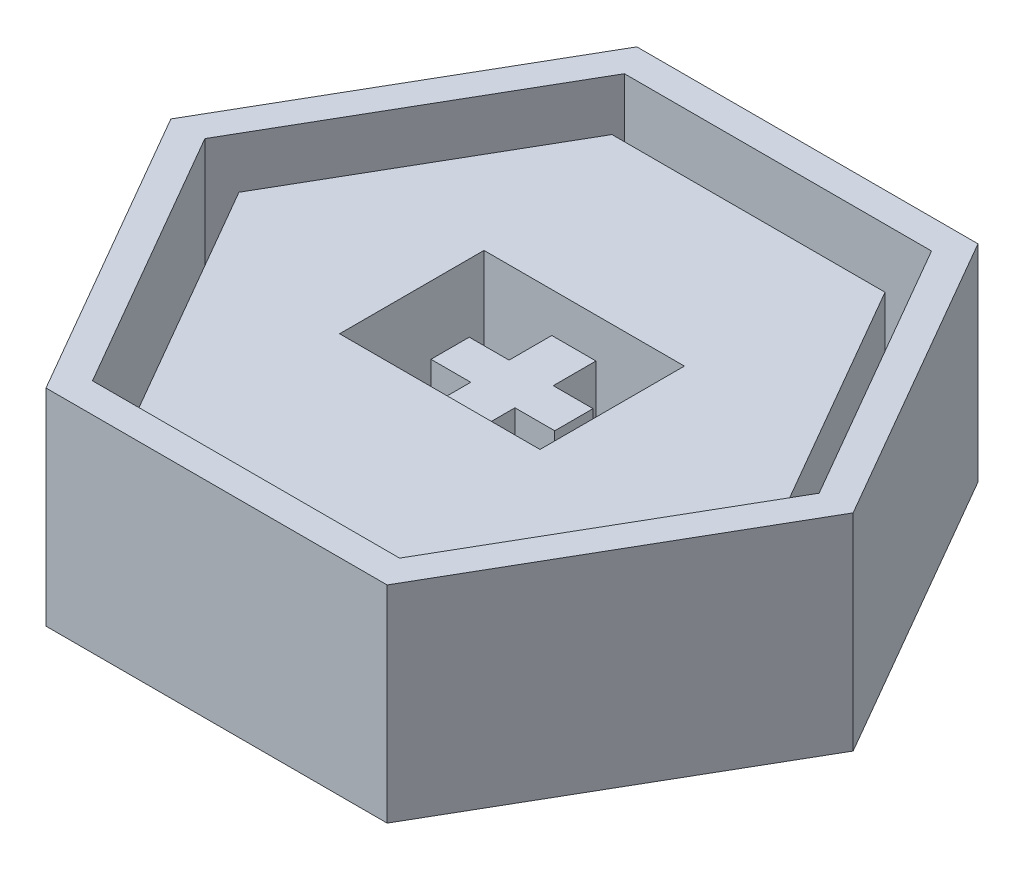
SolidWorks part; units mm, degrees
ref_plane "Plan de face" through (0, 0, 0) normal (0, 0, 1) x (1, 0, 0)
ref_plane "Plan de dessus" through (0, 0, 0) normal (0, 1, 0) x (1, 0, 0)
ref_plane "Plan de droite" through (0, 0, 0) normal (1, 0, 0) x (0, 0, -1)
sketch "Sketch1" plane through (0, 0, 0) normal (0, 1, 0) x (1, 0, 0)
  line L1 (10.4212, 0) -> (5.2106, 9.025)
  line L2 (5.2106, 9.025) -> (-5.2106, 9.025)
  line L3 (-5.2106, 9.025) -> (-10.4212, 0)
  line L4 (-10.4212, 0) -> (-5.2106, -9.025)
  line L5 (-5.2106, -9.025) -> (5.2106, -9.025)
  line L6 (5.2106, -9.025) -> (10.4212, 0)
  circle A0 centre (0, 0) radius 9.025 construction
  dimension "D1" = 18.05
extrude "Boss-Extrude1" add sketch "Sketch1" along normal blind 1
sketch "Sketch2" plane through (0, 0, 0) normal (0, -1, 0) x (1, 0, 0)
  line L1 (11.5759, 0) -> (5.7879, 10.025)
  line L2 (5.7879, 10.025) -> (-5.7879, 10.025)
  line L3 (-5.7879, 10.025) -> (-11.5759, 0)
  line L4 (-11.5759, 0) -> (-5.7879, -10.025)
  line L5 (-5.7879, -10.025) -> (5.7879, -10.025)
  line L6 (10.4212, 0) -> (5.2106, 9.025)
  line L7 (5.2106, 9.025) -> (-5.2106, 9.025)
  line L8 (-5.2106, 9.025) -> (-10.4212, 0)
  line L9 (-10.4212, 0) -> (-5.2106, -9.025)
  line L10 (-5.2106, -9.025) -> (5.2106, -9.025)
  line L11 (5.2106, -9.025) -> (10.4212, 0)
  line L12 (10.4212, 0) -> (5.2106, 9.025)
  line L13 (5.2106, 9.025) -> (-5.2106, 9.025)
  line L14 (-5.2106, 9.025) -> (-10.4212, 0)
  line L15 (-10.4212, 0) -> (-5.2106, -9.025)
  line L16 (-5.2106, -9.025) -> (5.2106, -9.025)
  line L17 (5.2106, -9.025) -> (10.4212, 0)
  line L18 (5.7879, -10.025) -> (11.5759, 0)
  dimension "D1" = 0
  dimension "D2" = 1
extrude "Boss-Extrude2" add sketch "Sketch2" against normal blind 7 separate body
sketch "Sketch3" plane through (0, 1, 0) normal (0, 1, 0) x (1, 0, 0)
  line L7 (-3.4, -2.45) -> (3.4, -2.45)
  line L8 (-3.4, -2.45) -> (-3.4, 2.45)
  line L9 (-3.4, 2.45) -> (3.4, 2.45)
  line L10 (3.4, -2.45) -> (3.4, 2.45)
  line L11 (-3.4, -2.45) -> (3.4, 2.45) construction
  line L12 (4.6332, -8.025) -> (9.2665, 0)
  line L13 (9.2665, 0) -> (4.6332, 8.025)
  line L14 (4.6332, 8.025) -> (-4.6332, 8.025)
  line L15 (-4.6332, 8.025) -> (-9.2665, 0)
  line L16 (-9.2665, 0) -> (-4.6332, -8.025)
  line L17 (-4.6332, -8.025) -> (4.6332, -8.025)
  line L18 (4.6332, -8.025) -> (9.2665, 0)
  line L19 (9.2665, 0) -> (4.6332, 8.025)
  line L20 (4.6332, 8.025) -> (-4.6332, 8.025)
  line L21 (-4.6332, 8.025) -> (-9.2665, 0)
  line L22 (-9.2665, 0) -> (-4.6332, -8.025)
  line L23 (-4.6332, -8.025) -> (4.6332, -8.025)
  line L24 (-3.4, 2.45) -> (3.4, -2.45) construction
  point P0 (0, 0)
  dimension "D2" = 6.8
  dimension "D3" = 4.9
  dimension "D1" = 1
extrude "Boss-Extrude3" add sketch "Sketch3" along normal offset from surface (5 mm away) 1 up to face at (0, 7, 0)
sketch "Sketch4" plane through (0, 1, 0) normal (0, 1, 0) x (1, 0, 0)
  line L0 (0, 2.1) -> (0, -2.1) construction
  line L1 (2.1, 0) -> (-2.1, 0) construction
  line L2 (-0.75, 2.1) -> (0.75, 2.1)
  line L3 (0.75, 2.1) -> (0.75, 0.65)
  line L4 (0.75, 0.65) -> (2.1, 0.65)
  line L5 (2.1, 0.65) -> (2.1, -0.65)
  line L6 (2.1, -0.65) -> (0.75, -0.65)
  line L7 (0.75, -0.65) -> (0.75, -2.1)
  line L8 (0.75, -2.1) -> (-0.75, -2.1)
  line L9 (-0.75, -2.1) -> (-0.75, -0.65)
  line L10 (-0.75, -0.65) -> (-2.1, -0.65)
  line L11 (-2.1, -0.65) -> (-2.1, 0.65)
  line L12 (-2.1, 0.65) -> (-0.75, 0.65)
  line L13 (-0.75, 0.65) -> (-0.75, 2.1)
  point P5 (0, 0)
  point P18 (0, 0)
  point P19 (0.9603, 1.5897)
  dimension "D1" = 1.5
  dimension "D2" = 1.3
  dimension "D3" = 4.2
extrude "Boss-Extrude4" add sketch "Sketch4" along normal offset from surface (4 mm away) 1 up to face at (0, 6, 0)
